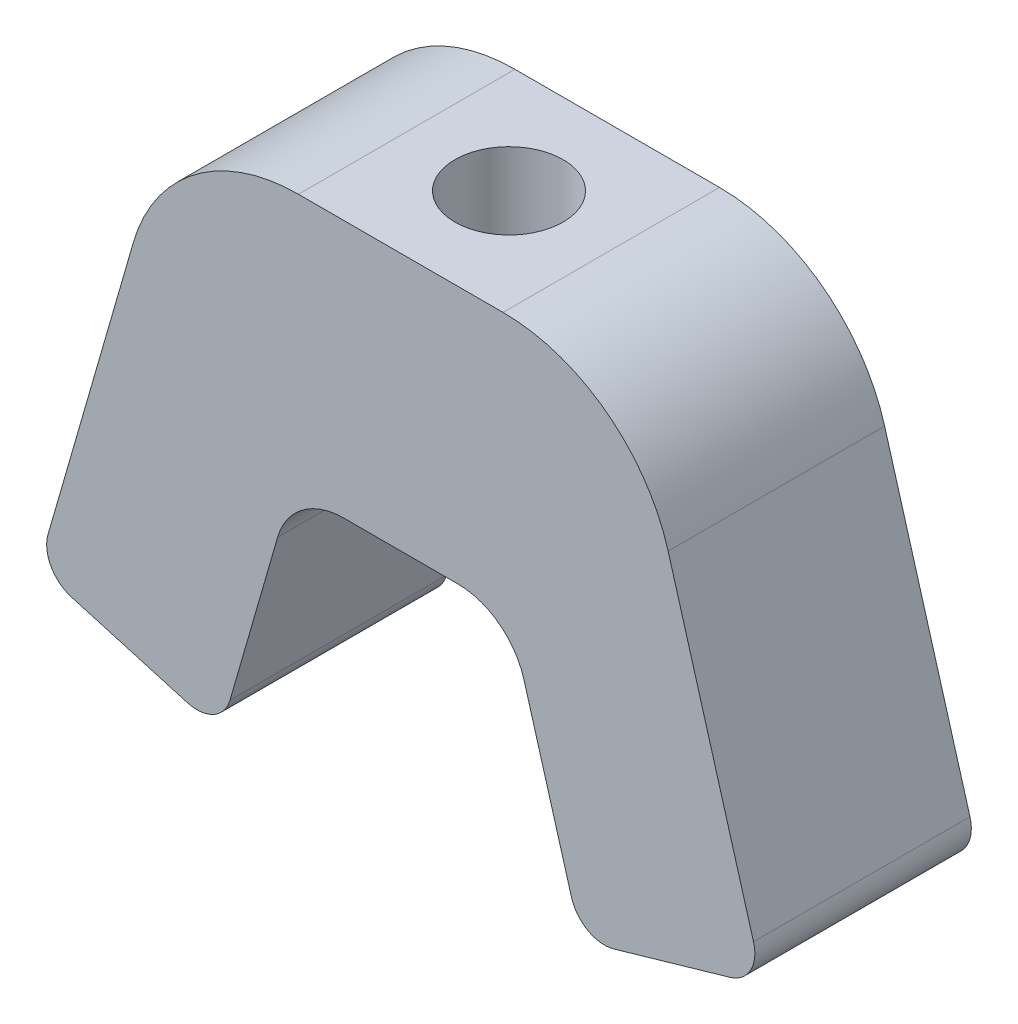
SolidWorks part; units mm, degrees
material "6061-T6 (SS)"
ref_plane "Front Plane" through (0, 0, 0) normal (0, 0, 1) x (1, 0, 0)
ref_plane "Top Plane" through (0, 0, 0) normal (0, 1, 0) x (1, 0, 0)
ref_plane "Right Plane" through (0, 0, 0) normal (1, 0, 0) x (0, 0, -1)
sketch "Sketch1" plane through (0, 0, 0) normal (0, 0, 1) x (1, 0, 0)
  line L0 (0, 0) -> (-22, -76.2) construction
  line L1 (-22, -76.2) -> (22, -76.2) construction
  line L2 (22, -76.2) -> (0, 0) construction
  line L3 (0, 0) -> (0, -76.2) construction
  line L4 (-13.3878, -33.7525) -> (-6.6625, -35.6942)
  line L5 (17.2795, -59.8498) -> (12.766, -61.1529) construction
  line L6 (-6.6625, -35.6942) -> (-4.0204, -26.543)
  line L9 (6.6625, -35.6942) -> (13.3878, -33.7525)
  line L11 (13.3878, -33.7525) -> (8.5563, -17.018)
  line L12 (8.5563, -17.018) -> (-8.5563, -17.018)
  line L13 (-8.5563, -17.018) -> (-13.3878, -33.7525)
  line L15 (-4.0204, -26.543) -> (4.0204, -26.543)
  line L16 (4.0204, -26.543) -> (6.6625, -35.6942)
  dimension "D1" = 44
  dimension "D2" = 76.2
  dimension "D3" = 3.5
  dimension "D4" = 3.5
  dimension "D5" = 3.5
  dimension "D6" = 17.018
  dimension "D7" = 3.5
  dimension "D8" = 9.525
  dimension "D9" = 9.525
  dimension "D10" = 17.018
extrude "Boss-Extrude1" add sketch "Sketch1" along normal blind 8
fillet "Fillet1" radius 6.35 2 edges at (-8.5563, -17.018, 4) (8.5563, -17.018, 4)
fillet "Fillet2" radius 2.54 2 edges at (4.0204, -26.543, 4) (-4.0204, -26.543, 4)
fillet "Fillet3" radius 1.27 4 edges at (13.3878, -33.7525, 4) (6.6625, -35.6942, 4) (-6.6625, -35.6942, 4) (-13.3878, -33.7525, 4)
hole_wizard "#8-32 Tapped Hole3" positions "3DSketch1" profile "Sketch8" tap size "#8-32" standard "ANSI Inch"
sketch3d "3DSketch1"
  line L0 (-7.8826, -35.342, 8) -> (-12.1676, -34.1048, 0) construction
  line L1 (12.1676, -34.1048, 8) -> (7.8826, -35.342, 0) construction
  line L2 (3.7803, -17.018, 0) -> (-3.7803, -17.018, 8) construction
  point P0 (-10.0251, -34.7234, 4)
  point P8 (10.0251, -34.7234, 4)
  point P16 (0, -17.018, 4)
sketch "Sketch8" plane through (-10.0251, -34.7234, 4) normal (0, 0, 1) x (0.9608, -0.2774, 0)
  line L0 (0, 0) -> (0, 11.9104)
  line L1 (0, 11.9104) -> (2, 10.7086)
  line L2 (2, 10.7086) -> (2, 0)
  line L5 (2, 0) -> (0, 0)
  line L10 (0, 11.9104) -> (-2, 10.7086) construction
  line L11 (0, -6.35) -> (0, 107.95) construction
  dimension "Tap Drill Dia." = 4
  dimension "Tap Drill Depth" = 10.7086
  dimension "Drill Angle" = 118
cosmetic thread "Hole Thread3" parameters "D1"=8.3312, "D2"=4.1656
cosmetic thread "Hole Thread4" parameters "D1"=8.3312, "D2"=4.1656
cosmetic thread "Hole Thread5" parameters "D1"=8.3312, "D2"=4.1656
